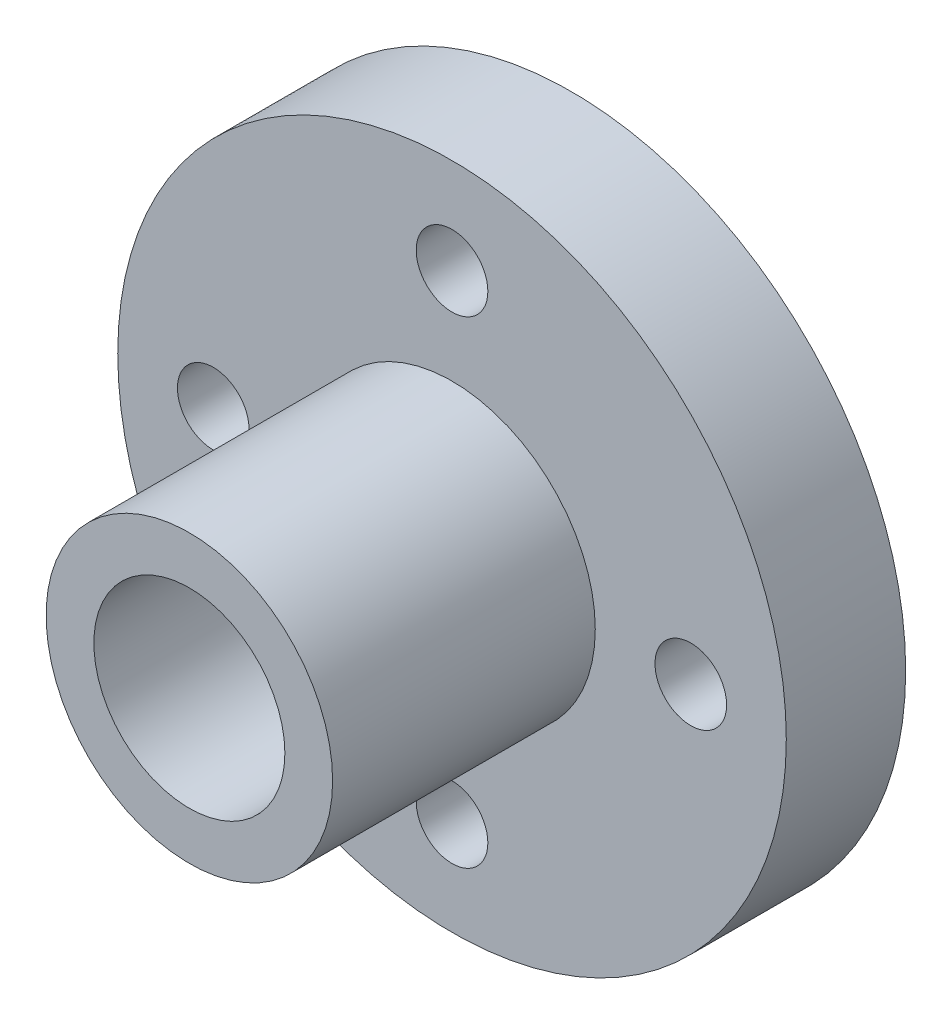
SolidWorks part; units mm, degrees
ref_plane "前视基准面" through (0, 0, 0) normal (0, 0, 1) x (1, 0, 0)
ref_plane "上视基准面" through (0, 0, 0) normal (0, 1, 0) x (1, 0, 0)
ref_plane "右视基准面" through (0, 0, 0) normal (1, 0, 0) x (0, 0, -1)
sketch "草图1" plane through (0, 0, 0) normal (0, 0, 1) x (1, 0, 0)
  circle A0 centre (0, 0) radius 14
  circle A2 centre (0, 0) radius 4
  circle A3 centre (0, 10) radius 1.5
  circle A4 centre (10, 0) radius 1.5
  circle A5 centre (0, -10) radius 1.5
  circle A6 centre (-10, 0) radius 1.5
extrude "凸台-拉伸1" add sketch "草图1" along normal blind 5
sketch "草图2" plane through (0, 0, 5) normal (0, 0, 1) x (1, 0, 0)
  circle A0 centre (0, 0) radius 4
  circle A1 centre (0, 0) radius 6
extrude "凸台-拉伸2" add sketch "草图2" along normal blind 11
